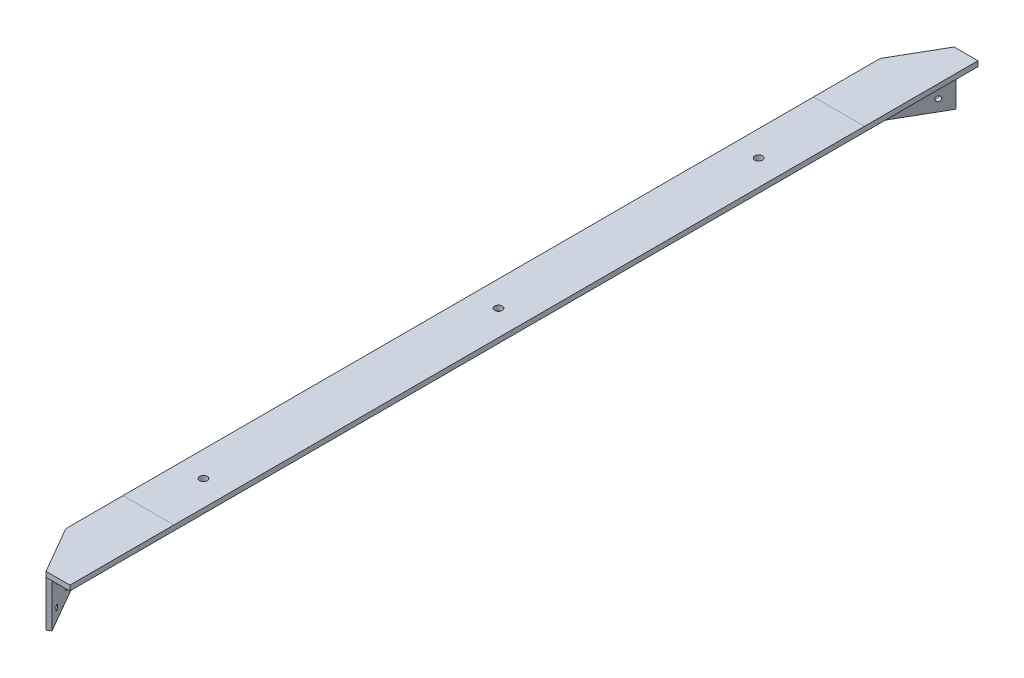
SolidWorks part; units mm, degrees
material "1.0116 (S235J2G3)"
ref_plane "Front Plane" through (0, 0, 0) normal (0, 0, 1) x (1, 0, 0)
ref_plane "Top Plane" through (0, 0, 0) normal (0, 1, 0) x (1, 0, 0)
ref_plane "Right Plane" through (0, 0, 0) normal (1, 0, 0) x (0, 0, -1)
sketch "Sketch1" plane through (0, 0, 0) normal (0, 0, 1) x (1, 0, 0)
  line L0 (-8, 8) -> (72, 8)
  line L1 (72, 8) -> (72, 0)
  line L2 (72, 0) -> (0, 0)
  line L3 (0, 0) -> (0, -72)
  line L4 (0, -72) -> (-8, -72)
  line L5 (-8, -72) -> (-8, 8)
  dimension "D1" = 80
  dimension "D2" = 80
  dimension "D3" = 8
  dimension "D4" = 8
extrude "Boss-Extrude1" add sketch "Sketch1" along normal blind 640
sketch "Sketch3" plane through (0, 0, 0) normal (0, 1, 0) x (1, 0, 0)
  line L0 (-8, -640) -> (34.5, -713.6122)
  line L1 (34.5, -713.6122) -> (72, -713.6122)
  line L2 (72, -713.6122) -> (72, -640)
  line L3 (72, -640) -> (-8, -640)
  line L4 (-8, -640) -> (-8, 0) construction
  dimension "D1" = 210
  dimension "D2" = 85
extrude "Boss-Extrude2" add sketch "Sketch3" along normal blind 8
sketch "Sketch4" plane through (0, 0, 0) normal (0, -1, 0) x (1, 0, 0)
  line L0 (-8, 640) -> (34.5, 713.6122)
  line L1 (34.5, 713.6122) -> (40.5, 710.1481)
  line L2 (40.5, 710.1481) -> (0, 640)
  line L3 (-8, 640) -> (0, 640) construction
  line L4 (0, 640) -> (-8, 640)
  dimension "D1" = 8
extrude "Boss-Extrude3" add sketch "Sketch4" along normal blind 72
sketch "Sketch6" plane through (-277.1281, 0, 160) normal (0.866, 0, -0.5) x (-0.5, 0, -0.866)
  line L0 (-635.2563, -36) -> (-554.2563, -36) construction
  line L1 (-635.2563, -72) -> (-635.2563, 0) construction
  line L2 (-554.2563, -72) -> (-554.2563, 0) construction
  line L3 (-594.7563, 0) -> (-594.7563, -72) construction
  line L4 (-554.2563, 0) -> (-635.2563, 0) construction
  line L5 (-554.2563, -72) -> (-635.2563, -72) construction
  circle A0 centre (-615.0063, -18) radius 4
  circle A1 centre (-574.5063, -18) radius 4
  circle A2 centre (-574.5063, -54) radius 4
  circle A3 centre (-615.0063, -54) radius 4
  dimension "D1" = 20.25
  dimension "D3" = 8
  dimension "D2" = 18
extrude "Cut-Extrude1" cut sketch "Sketch6" against normal blind 8
fillet "Fillet1" radius 10 2 edges at (-8, -32, 640) (0, -36, 640)
fillet "Fillet2" radius 8 3 edges at (0, 0, 318.6603) (0.3407, 0, 639.9087) (20.9199, 0, 676.2343)
mirror "Mirror1" about plane through (0, 0, 0) normal (0, 0, 1) of "Boss-Extrude1", "Boss-Extrude2", "Boss-Extrude3", "Cut-Extrude1", "Fillet1", "Fillet2"
sketch "Sketch7" plane through (0, 8, 0) normal (0, 1, 0) x (1, 0, 0)
  line L0 (-8, 535.2362) -> (72, 535.2362)
  line L1 (-8, -637.3205) -> (-8, 637.3205) construction
  line L2 (72, -713.6122) -> (72, 713.6122) construction
  line L3 (72, 535.2362) -> (72, -550.1105)
  line L4 (72, -550.1105) -> (-8, -550.1105)
  line L5 (-8, -550.1105) -> (-8, 535.2362)
  point P6 (0, 0)
  point P9 (0, 0)
  dimension "D1" = 102.0843
  dimension "D2" = 87.21
split line "Split Line1"
sketch "Sketch8" plane through (0, 8, 0) normal (0, 1, 0) x (1, 0, 0)
  line L0 (34.5, -713.6122) -> (72, -713.6122) construction
  line L1 (-8, -550.1105) -> (-8, 535.2362) construction
  line L2 (34.5, 713.6122) -> (72, 713.6122) construction
  circle A0 centre (32, 408.8899) radius 6
  circle A1 centre (32, 0) radius 6
  circle A2 centre (32, -463.6122) radius 6
  dimension "D1" = 12
  dimension "D2" = 12
  dimension "D3" = 12
  dimension "D4" = 250
  dimension "D5" = 40
  dimension "D6" = 40
  dimension "D7" = 40
  dimension "D8" = 304.7223
  dimension "D9" = 713.6122
extrude "Cut-Extrude2" cut sketch "Sketch8" against normal blind 8
